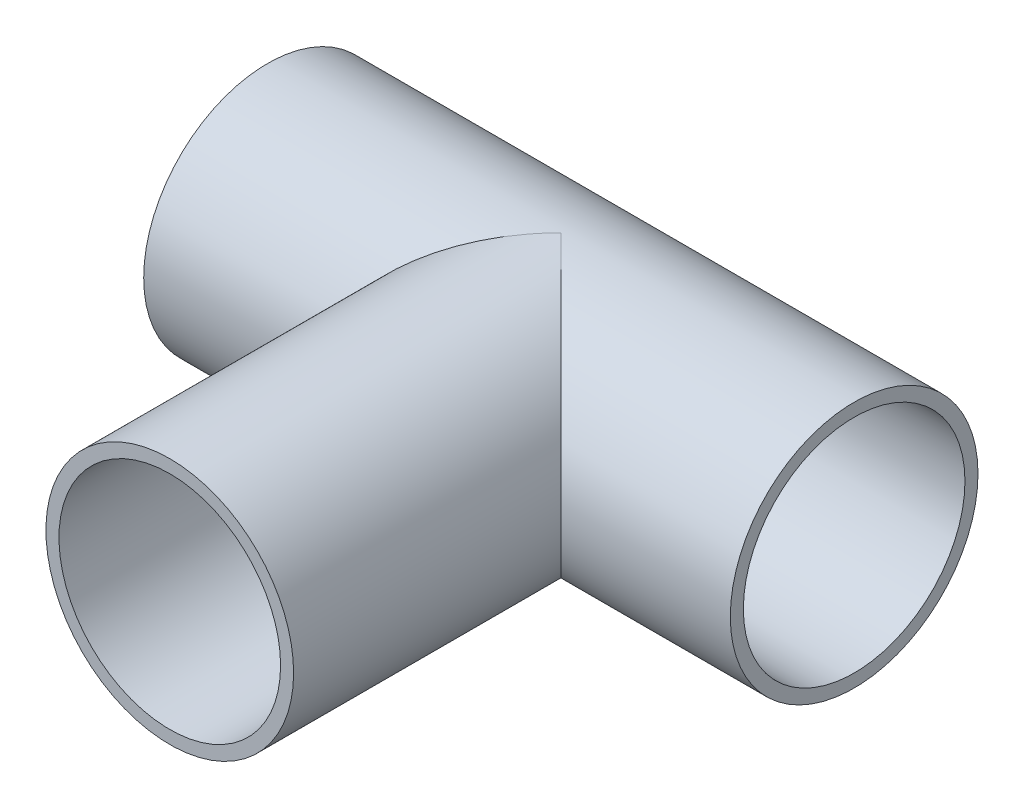
SolidWorks part; units mm, degrees
ref_plane "Front Plane" through (0, 0, 0) normal (0, 0, 1) x (1, 0, 0)
ref_plane "Top Plane" through (0, 0, 0) normal (0, 1, 0) x (1, 0, 0)
ref_plane "Right Plane" through (0, 0, 0) normal (1, 0, 0) x (0, 0, -1)
sketch "Sketch1" plane through (0, 0, 0) normal (0, 0, 1) x (1, 0, 0)
  circle A0 centre (0, 0) radius 17
  circle A1 centre (0, 0) radius 19
  dimension "D1" = 34
  dimension "D2" = 2
sketch "Sketch2" plane through (0, 0, 0) normal (0, 1, 0) x (1, 0, 0)
  line L0 (0, 0) -> (0, 60)
  line L1 (0, 60) -> (-45, 60)
  point P6 (0, 60)
  dimension "D2" = 45
  dimension "D1" = 60
sweep "Sweep1" add profiles "Sketch1" path "Sketch2"
mirror "Mirror1" about plane through (0, 0, 0) normal (1, 0, 0) of bodies 102
sketch "Sketch3" plane through (0, 0, 0) normal (1, 0, 0) x (0, 0, -1)
  circle A0 centre (60, 0) radius 17
extrude "Cut-Extrude1" cut sketch "Sketch3" against normal through all both and the other way through all
